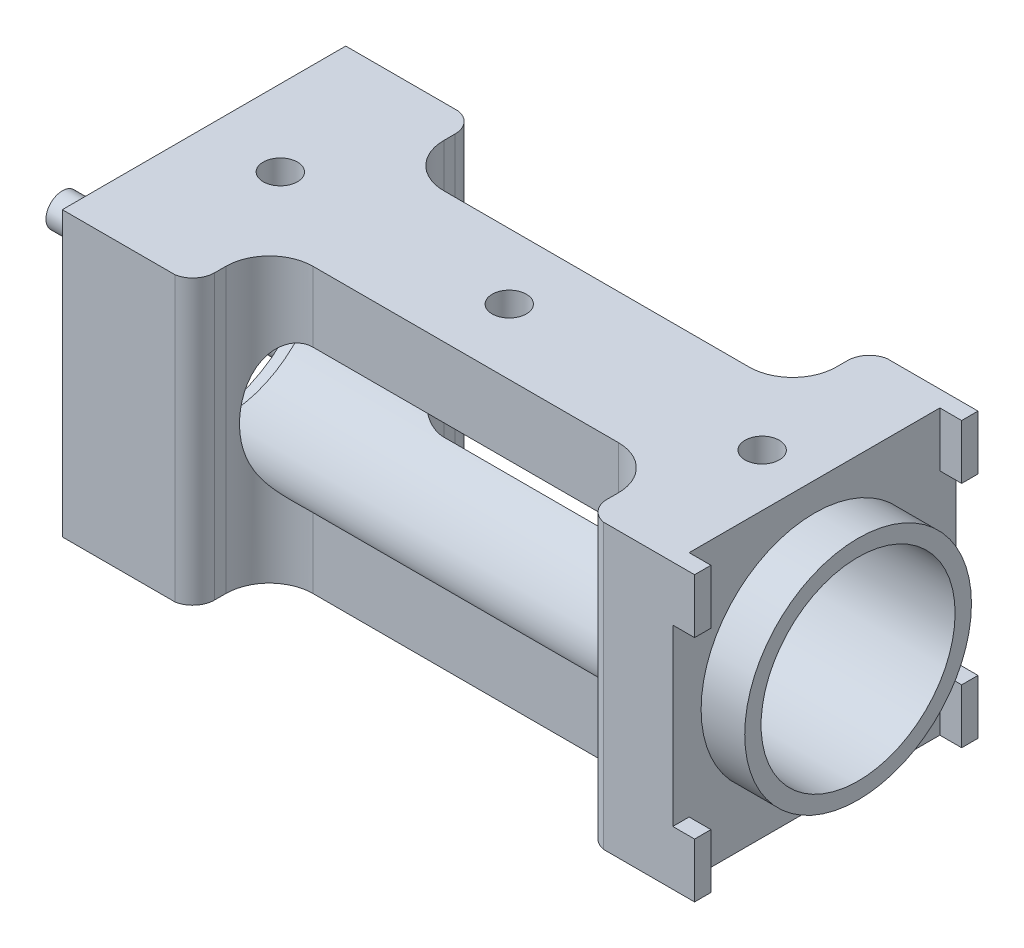
SolidWorks part; units mm, degrees
ref_plane "前视基准面" through (0, 0, 0) normal (0, 0, 1) x (1, 0, 0)
ref_plane "上视基准面" through (0, 0, 0) normal (0, 1, 0) x (1, 0, 0)
ref_plane "右视基准面" through (0, 0, 0) normal (1, 0, 0) x (0, 0, -1)
sketch "草图1" plane through (0, 0, 0) normal (0, 0, 1) x (1, 0, 0)
  line L0 (-99.1899, 0) -> (107.5443, 0) construction
  line L1 (0, 54.2278) -> (0, -50.2785) construction
  line L2 (0, 0) -> (60, 0)
  dimension "D1" = 60
sketch "草图2" plane through (0, 0, 0) normal (1, 0, 0) x (0, 0, -1)
  line L0 (-54.7753, 0) -> (48.4944, 0) construction
  line L2 (-13, 13) -> (13, 13)
  line L3 (-13, 13) -> (-13, -13)
  line L4 (-13, -13) -> (13, -13)
  line L5 (13, 13) -> (13, -13)
  line L6 (0, -13) -> (0, 13) construction
  line L7 (-13, 0) -> (13, 0) construction
  circle A0 centre (0, 0) radius 8.9
  point P3 (0, 0)
  dimension "D1" = 26
  dimension "D2" = 26
sweep "摩擦轮管" add profiles "草图2" path "草图1"
sketch "草图3" plane through (0, 0, 0) normal (1, 0, 0) x (0, 0, -1)
  line L0 (-19.6545, 0) -> (23.1822, 0) construction
  line L1 (0, 13.6069) -> (0, -14.217) construction
  circle A0 centre (-10, 10) radius 1.5
  circle A1 centre (10, -10) radius 1.5
  dimension "D1" = 10
  dimension "D3" = 10
  dimension "D2" = 10
  dimension "D4" = 10
extrude "枪管固定" add sketch "草图3" against normal blind 3
sketch "草图4" plane through (0, 0, 0) normal (1, 0, 0) x (0, 0, -1)
  circle A0 centre (0, 0) radius 10.4
extrude "切除-拉伸1" cut sketch "草图4" along normal blind 2
sketch "草图5" plane through (0, 0, 0) normal (0, 1, 0) x (1, 0, 0)
  line L0 (-18.8292, 0) -> (70.7139, 0) construction
  line L1 (30, 23.6894) -> (30, -21.2063) construction
  line L3 (0, -13) -> (60, -13) construction
  line L4 (12, -11.0305) -> (12, -10)
  line L5 (16, -6) -> (44, -6)
  line L6 (48, -10) -> (48, -11.0305)
  line L7 (50, -13.0305) -> (10, -13.0305)
  line L8 (48, 10) -> (48, 11.0305)
  line L9 (12, 11.0305) -> (12, 10)
  line L10 (50, 13.0305) -> (10, 13.0305)
  line L11 (16, 6) -> (44, 6)
  line L12 (0, -13.0305) -> (10, -13.0305) construction
  line L13 (50, -13.0305) -> (53.6373, -13.0305) construction
  arc A0 (12, -10) -> (16, -6) centre (16, -10) cw
  arc A1 (44, -6) -> (48, -10) centre (44, -10) cw
  arc A2 (50, 13.0305) -> (48, 11.0305) centre (50, 11.0305) ccw
  arc A3 (44, 6) -> (48, 10) centre (44, 10) ccw
  arc A4 (10, -13.0305) -> (12, -11.0305) centre (10, -11.0305) ccw
  arc A5 (50, -13.0305) -> (48, -11.0305) centre (50, -11.0305) cw
  arc A6 (10, 13.0305) -> (12, 11.0305) centre (10, 11.0305) cw
  arc A7 (12, 10) -> (16, 6) centre (16, 10) ccw
  point P8 (30, -13)
  point P15 (12, -6)
  point P18 (48, -6)
  dimension "D3" = 4
  dimension "D4" = 4
  dimension "D5" = 2
  dimension "D2" = 2
  dimension "D1" = 28
  dimension "D6" = 40
extrude "摩擦轮口" cut sketch "草图5" against normal through all and the other way through all
ref_plane "基准面1" through (60, 0, 0) normal (1, 0, 0) x (0, 0, -1)
sketch "草图6" plane through (60, 0, 0) normal (1, 0, 0) x (0, 0, -1)
  line L0 (-19.8985, 0) -> (25.9672, 0) construction
  line L1 (0, 15.3761) -> (0, -16.2514) construction
  line L2 (-13, 8) -> (-11.5, 8)
  line L3 (-13, 13) -> (-13, -13) construction
  line L4 (-11.5, 8) -> (-11.5, 13)
  line L5 (13, 13) -> (-13, 13) construction
  line L6 (-11.5, 13) -> (11.5, 13)
  line L7 (-13, 8) -> (-13, -8)
  line L8 (13, 8) -> (13, -8)
  line L9 (13, 8) -> (11.5, 8)
  line L10 (11.5, 8) -> (11.5, 13)
  line L11 (13, -8) -> (11.5, -8)
  line L12 (11.5, -8) -> (11.5, -13)
  line L13 (-11.5, -13) -> (11.5, -13)
  line L14 (-11.5, -8) -> (-11.5, -13)
  line L15 (-13, -8) -> (-11.5, -8)
  circle A0 centre (0, 0) radius 10.4
  point P21 (0, 13)
  point P22 (13, 0)
  point P27 (-13, 0)
  dimension "D1" = 5
  dimension "D2" = 1.5
extrude "切除-拉伸3" cut sketch "草图6" against normal blind 4
sketch "草图7" plane through (60, 0, 0) normal (1, 0, 0) x (0, 0, -1)
  line L0 (-25.929, 0) -> (28.3338, 0) construction
  line L1 (0, 17.5856) -> (0, -19.6316) construction
  line L2 (-13, 8) -> (-11.5, 8)
  line L3 (-11.5, 8) -> (-11.5, 13)
  line L4 (-11.5, 13) -> (-13, 13)
  line L5 (-13, 13) -> (-13, 8)
  line L6 (-11.5, 13) -> (-13, 13) construction
  line L7 (11.5, 13) -> (13, 13)
  line L8 (13, 8) -> (11.5, 8)
  line L9 (13, 13) -> (13, 8)
  line L10 (11.5, 8) -> (11.5, 13)
  line L11 (13, -13) -> (13, -8)
  line L12 (11.5, -13) -> (13, -13)
  line L13 (11.5, -8) -> (11.5, -13)
  line L14 (13, -8) -> (11.5, -8)
  line L15 (-11.5, -13) -> (-13, -13)
  line L16 (-11.5, -8) -> (-11.5, -13)
  line L17 (-13, -13) -> (-13, -8)
  line L18 (-13, -8) -> (-11.5, -8)
  dimension "D1" = 1.5
  dimension "D2" = 5
extrude "切除-拉伸4" cut sketch "草图7" against normal blind 2
sketch "草图8" plane through (0, 0, 0) normal (0, 1, 0) x (1, 0, 0)
  line L0 (-14.4092, 0) -> (74.1903, 0) construction
  line L1 (56, 11.5) -> (56, -11.5) construction
  circle A0 centre (7, 0) radius 1.57
  circle A1 centre (28, 0) radius 1.57
  circle A2 centre (51.2, 0) radius 1.57
  point P11 (0, 0)
  dimension "D1" = 7
  dimension "D2" = 51.2
  dimension "D3" = 28
  dimension "D4" = 56
extrude "上板螺孔" cut sketch "草图8" along normal through all
cosmetic thread "装饰螺纹线1" parameters "D2"=9.42
cosmetic thread "装饰螺纹线2" parameters "D2"=9.42
cosmetic thread "装饰螺纹线3" parameters "D2"=9.42
sketch "草图9" plane through (0, 0, 0) normal (1, 0, 0) x (0, 0, -1)
  line L0 (20.0376, 0) -> (-19.5503, 0) construction
  line L1 (0, 12.7511) -> (0, -13.6459) construction
  circle A0 centre (10, 10) radius 1.5
  circle A1 centre (-10, -10) radius 1.5
  dimension "D1" = 10
  dimension "D2" = 10
  dimension "D3" = 10
  dimension "D4" = 10
extrude "枪管固定螺孔" cut sketch "草图9" along normal blind 4
cosmetic thread "装饰螺纹线4" parameters "D2"=9
cosmetic thread "装饰螺纹线5" parameters "D2"=9
